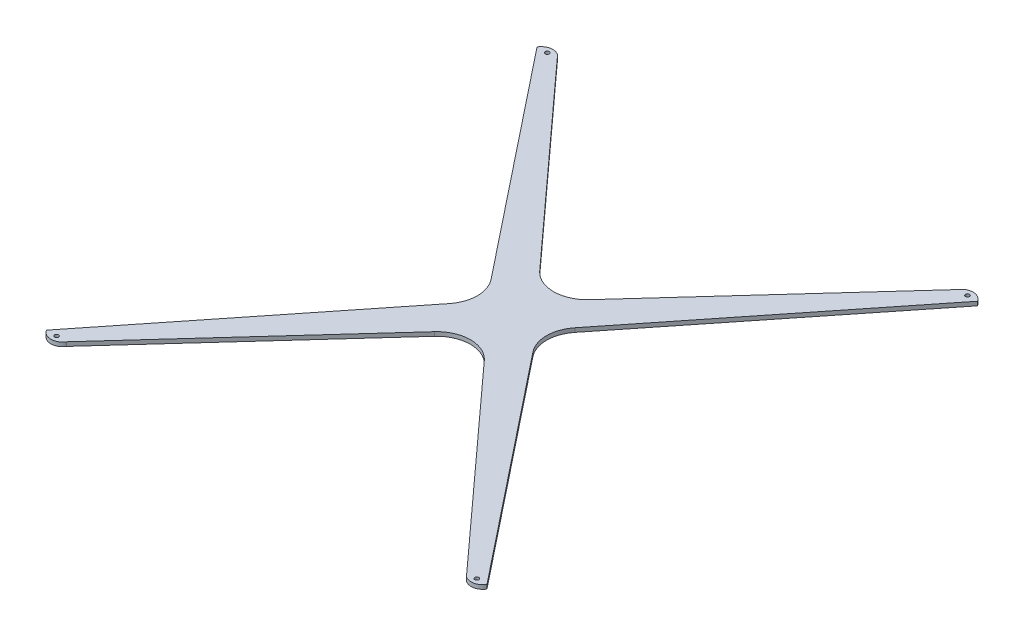
SolidWorks part; units mm, degrees
ref_plane "Front Plane" through (0, 0, 0) normal (0, 0, 1) x (1, 0, 0)
ref_plane "Top Plane" through (0, 0, 0) normal (0, 1, 0) x (1, 0, 0)
ref_plane "Right Plane" through (0, 0, 0) normal (1, 0, 0) x (0, 0, -1)
sketch "Sketch1" plane through (0, 0, 0) normal (0, 1, 0) x (1, 0, 0)
  line L0 (0, 0) -> (1250, 1459) construction
  line L1 (0, 0) -> (1250, 0) construction
  line L2 (0, 0) -> (0, 1459) construction
  line L3 (0, 1459) -> (1250, 1459) construction
  line L4 (1250, 0) -> (1250, 1459) construction
  line L5 (0, 1459) -> (1250, 0) construction
  line L6 (-30, 1459) -> (30, 1459) construction
  line L7 (1220, 1459) -> (1280, 1459) construction
  line L8 (1220, 0) -> (1280, 0) construction
  line L9 (-30, 0) -> (30, 0) construction
  line L10 (625, 654.5) -> (625, 804.5) construction
  line L11 (550, 729.5) -> (700, 729.5) construction
  line L12 (550, 729.5) -> (-30, 1459)
  line L13 (30, 1459) -> (625, 804.5)
  line L14 (625, 804.5) -> (1220, 1459)
  line L15 (550, 729.5) -> (-30, 0)
  line L16 (30, 0) -> (625, 654.5)
  line L17 (625, 654.5) -> (1220, 0)
  line L18 (1280, 0) -> (700, 729.5)
  line L19 (700, 729.5) -> (1280, 1459)
  line L20 (0, 1459) -> (0, 1476) construction
  circle A0 centre (0, 1459) radius 6
  circle A1 centre (1250, 1459) radius 6
  circle A2 centre (1250, 0) radius 6
  circle A3 centre (0, 0) radius 6
  arc A4 (-30, 1459) -> (30, 1459) centre (0, 1441.0294) cw
  arc A5 (1280, 1459) -> (1220, 1459) centre (1250, 1441.0294) ccw
  arc A6 (-30, 0) -> (30, 0) centre (0, 17.9706) ccw
  arc A7 (1280, 0) -> (1220, 0) centre (1250, 17.9706) cw
  point P15 (625, 729.5)
  dimension "D6" = 12
  dimension "D1" = 1459
  dimension "D2" = 1250
  dimension "D3" = 60
  dimension "D4" = 150
  dimension "D5" = 150
  dimension "D7" = 17
extrude "Boss-Extrude1" add sketch "Sketch1" along normal blind 12
fillet "Fillet1" radius 100 4 edges at (550, 6, -729.5) (625, 6, -804.5) (700, 6, -729.5) (625, 6, -654.5)
equation "\"mbtOD\" = 850"
equation "\"mbtT\" = 6"
equation "\"mbtL\" = 1500"
equation "\"mbtFlangeOD\" = 950"
equation "\"mbtFlangeT\" = 12"
equation "\"mbtFlangeBoltCircleDia\" = 650"
equation "\"mbtFlangeHoleDia\" = 12"
equation "\"mbtOringSize\" = 10 "
equation "\"mbtOringDia\" = 620"
equation "\"mbtWidth\" = 2250"
equation "\"skiWidth\" = 1250"
equation "\"D1@Sketch1\"=\"mbtL\"+2*\"mbtFlangeT\"-65mm"
equation "\"D2@Sketch1\"=\"skiWidth\""
equation "\"D1@Boss-Extrude1\"=\"mbtFlangeT\""
